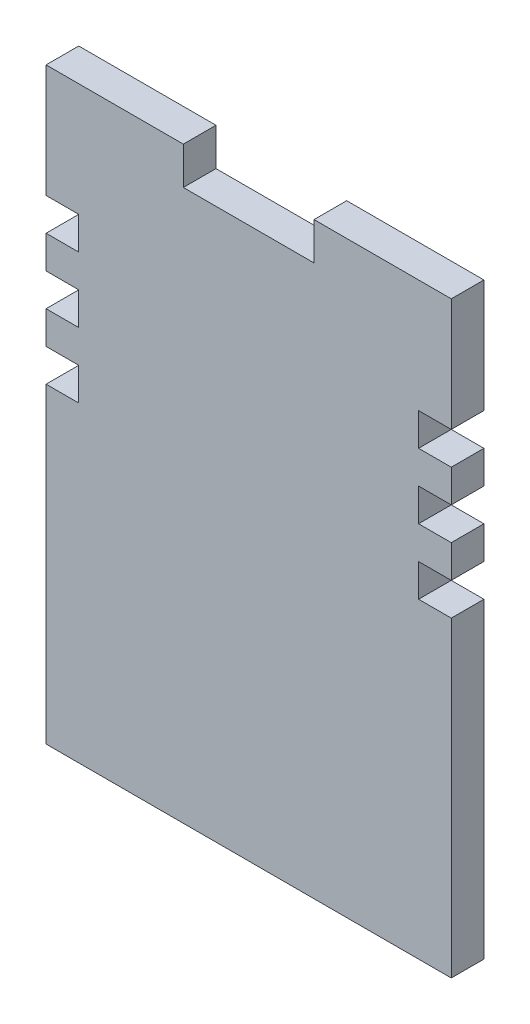
SolidWorks part; units mm, degrees
ref_plane "Plan de face" through (0, 0, 0) normal (0, 0, 1) x (1, 0, 0)
ref_plane "Plan de dessus" through (0, 0, 0) normal (0, 1, 0) x (1, 0, 0)
ref_plane "Plan de droite" through (0, 0, 0) normal (1, 0, 0) x (0, 0, -1)
sketch "Esquisse2" plane through (0, 0, 0) normal (0, 0, 1) x (1, 0, 0)
  line L97 (61.436, 160.0452) -> (61.436, 76.8543) construction
  line L98 (61.436, 76.8543) -> (61.436, 160.0452) construction
  line L99 (71.436, 161.1087) -> (51.436, 161.1087)
  line L100 (51.436, 161.1087) -> (51.436, 166.8543)
  line L101 (51.436, 166.8543) -> (30.436, 166.8543)
  line L102 (30.436, 166.8543) -> (30.436, 149.5443)
  line L103 (30.436, 149.5443) -> (35.436, 149.5443)
  line L104 (35.436, 149.5443) -> (35.436, 144.5443)
  line L105 (35.436, 144.5443) -> (30.436, 144.5443)
  line L106 (30.436, 144.5443) -> (30.436, 139.5443)
  line L107 (30.436, 139.5443) -> (35.436, 139.5443)
  line L108 (35.436, 139.5443) -> (35.436, 134.5443)
  line L109 (35.436, 134.5443) -> (30.436, 134.5443)
  line L110 (30.436, 134.5443) -> (30.436, 129.5443)
  line L111 (30.436, 129.5443) -> (35.436, 129.5443)
  line L112 (35.436, 129.5443) -> (35.436, 124.5443)
  line L113 (35.436, 124.5443) -> (30.436, 124.5443)
  line L114 (30.436, 124.5443) -> (30.436, 76.8543)
  line L133 (92.436, 124.5443) -> (92.436, 76.8543)
  line L134 (87.436, 124.5443) -> (92.436, 124.5443)
  line L135 (87.436, 129.5443) -> (87.436, 124.5443)
  line L136 (92.436, 129.5443) -> (87.436, 129.5443)
  line L137 (92.436, 134.5443) -> (92.436, 129.5443)
  line L138 (87.436, 134.5443) -> (92.436, 134.5443)
  line L139 (87.436, 139.5443) -> (87.436, 134.5443)
  line L140 (92.436, 139.5443) -> (87.436, 139.5443)
  line L141 (92.436, 144.5443) -> (92.436, 139.5443)
  line L142 (87.436, 144.5443) -> (92.436, 144.5443)
  line L143 (87.436, 149.5443) -> (87.436, 144.5443)
  line L144 (92.436, 149.5443) -> (87.436, 149.5443)
  line L145 (92.436, 166.8543) -> (92.436, 149.5443)
  line L146 (71.436, 166.8543) -> (92.436, 166.8543)
  line L147 (71.436, 161.1087) -> (71.436, 166.8543)
  line L148 (30.436, 76.8543) -> (61.436, 76.8543)
  line L149 (61.436, 76.8543) -> (92.436, 76.8543)
  point P50 (61.436, 161.1087)
  dimension "D3" = 5
  dimension "D2" = 17.31
  dimension "D4" = 5
  dimension "D7" = 31
  dimension "D8" = 10
extrude "Boss.-Extru.1" add sketch "Esquisse2" along normal blind 5
